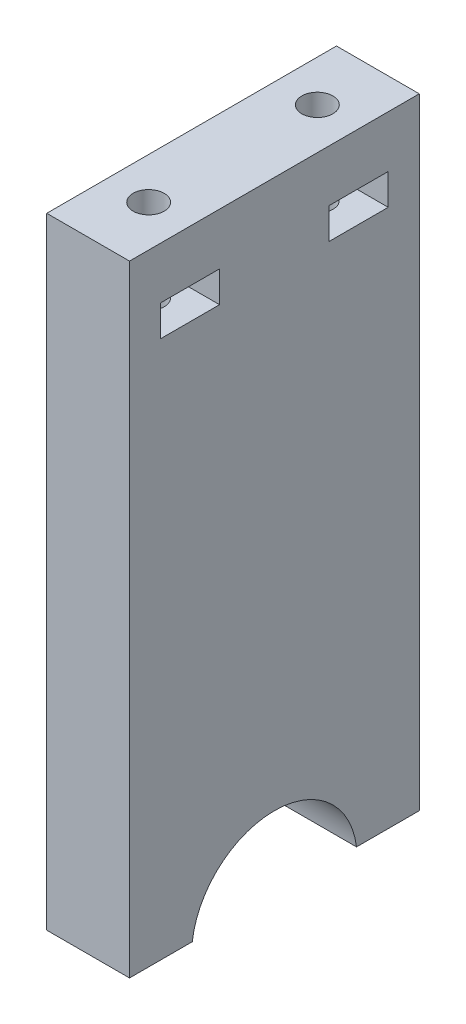
SolidWorks part; units mm, degrees
ref_plane "Front Plane" through (0, 0, 0) normal (0, 0, 1) x (1, 0, 0)
ref_plane "Top Plane" through (0, 0, 0) normal (0, 1, 0) x (1, 0, 0)
ref_plane "Right Plane" through (0, 0, 0) normal (1, 0, 0) x (0, 0, -1)
sketch "Sketch1" plane through (0, 0, 0) normal (0, 1, 0) x (1, 0, 0)
  line L1 (2, 21.8496) -> (10, 21.8496)
  line L2 (2, 21.8496) -> (2, -6.1504)
  line L3 (2, -6.1504) -> (10, -6.1504)
  line L4 (10, 21.8496) -> (10, -6.1504)
  dimension "D1" = 8
  dimension "D2" = 28
extrude "Boss-Extrude2" add sketch "Sketch1" along normal blind 60
sketch "Sketch5" plane through (10, 0, 0) normal (1, 0, 0) x (0, 0, -1)
  line L0 (21.8496, 0) -> (-6.1504, 0) construction
  line L1 (-6.1504, 60) -> (-6.1504, 0) construction
  line L2 (-0.0877, 0) -> (15.7868, 0)
  arc A0 (15.7868, 0) -> (-0.0877, 0) centre (7.8496, -1) ccw
  dimension "D1" = 16
  dimension "D3" = 14
  dimension "D2" = 1
extrude "Cut-Extrude2" cut sketch "Sketch5" against normal through all
sketch "Sketch6" plane through (0, 0, 0) normal (0, -1, 0) x (1, 0, 0)
  line L0 (2, -21.8496) -> (2, 6.1504) construction
  line L1 (2, -21.8496) -> (10, -21.8496) construction
  line L2 (2, 6.1504) -> (10, 6.1504) construction
  circle A0 centre (6, -18.3496) radius 1.5
  circle A1 centre (6, 2.6504) radius 1.5
  dimension "D1" = 3
  dimension "D2" = 4
  dimension "D3" = 3.5
  dimension "D4" = 3
  dimension "D5" = 4
  dimension "D6" = 3.5
extrude "Cut-Extrude3" cut sketch "Sketch6" against normal blind 25
sketch "Sketch7" plane through (2, 0, 0) normal (-1, 0, 0) x (0, 0, 1)
  line L0 (-21.8496, 60) -> (6.1504, 60) construction
  line L1 (-18.8496, 52) -> (-13.1496, 52)
  line L2 (-18.8496, 52) -> (-18.8496, 55)
  line L3 (-18.8496, 55) -> (-13.1496, 55)
  line L4 (-13.1496, 52) -> (-13.1496, 55)
  line L5 (-2.5496, 52) -> (3.1504, 52)
  line L6 (-2.5496, 52) -> (-2.5496, 55)
  line L7 (-2.5496, 55) -> (3.1504, 55)
  line L8 (3.1504, 52) -> (3.1504, 55)
  line L9 (-21.8496, 60) -> (-21.8496, 0) construction
  line L10 (6.1504, 60) -> (6.1504, 0) construction
  dimension "D1" = 5.7
  dimension "D2" = 5.7
  dimension "D3" = 5
  dimension "D4" = 5
  dimension "D5" = 3
  dimension "D6" = 3
  dimension "D7" = 3
  dimension "D8" = 3
extrude "Cut-Extrude4" cut sketch "Sketch7" against normal through all
sketch "Sketch8" plane through (0, 60, 0) normal (0, 1, 0) x (1, 0, 0)
  line L0 (10, 21.8496) -> (2, 21.8496) construction
  line L1 (10, -6.1504) -> (10, 21.8496) construction
  line L2 (2, -6.1504) -> (10, -6.1504) construction
  circle A0 centre (6, 15.9996) radius 1.5
  circle A2 centre (6, -0.3004) radius 1.5
  dimension "D1" = 5.85
  dimension "D2" = 4
  dimension "D3" = 3
  dimension "D4" = 5.85
  dimension "D5" = 4
  dimension "D6" = 3
extrude "Cut-Extrude5" cut sketch "Sketch8" against normal blind 25
